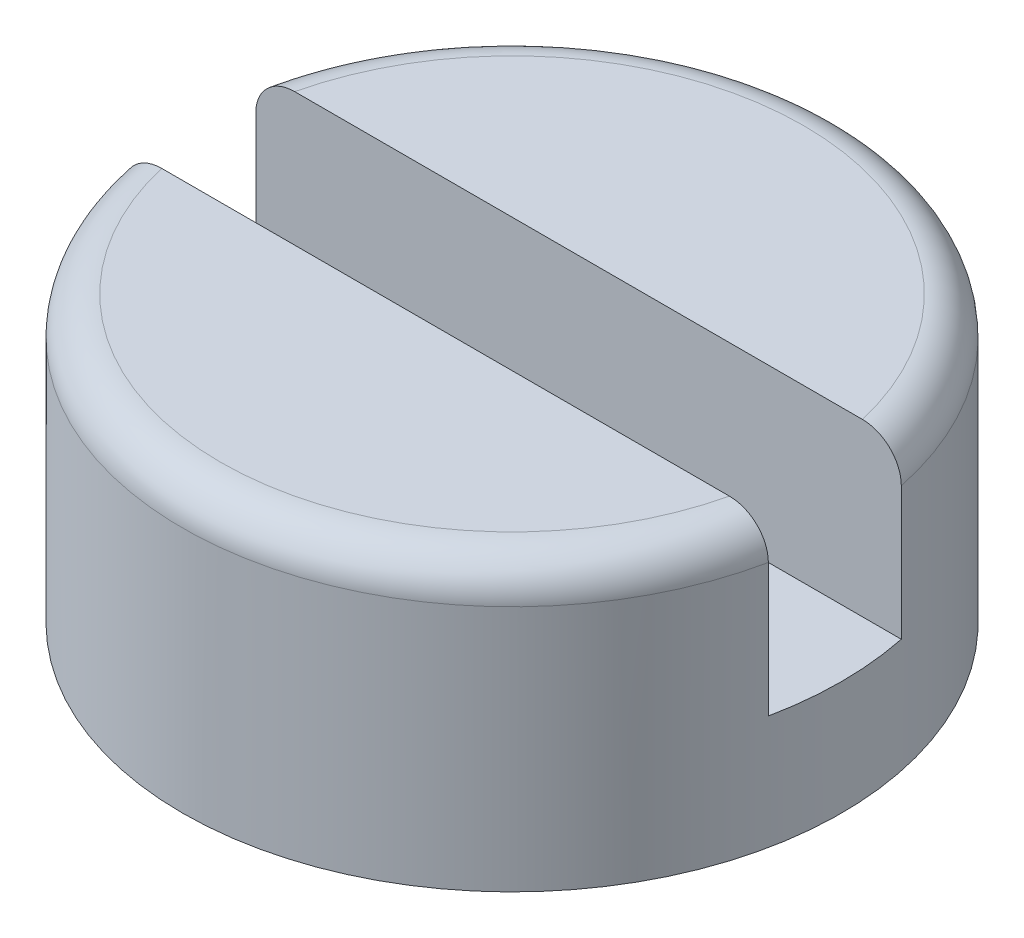
SolidWorks part; units mm, degrees
ref_plane "Спереди" through (0, 0, 0) normal (0, 0, 1) x (1, 0, 0)
ref_plane "Сверху" through (0, 0, 0) normal (0, 1, 0) x (1, 0, 0)
ref_plane "Справа" through (0, 0, 0) normal (1, 0, 0) x (0, 0, -1)
sketch "Эскиз1" plane through (0, 0, 0) normal (0, 1, 0) x (1, 0, 0)
  circle A0 centre (0, 0) radius 1.735
  dimension "D1" = 3.47
extrude "Бобышка-Вытянуть1" add sketch "Эскиз1" along normal blind 1.5
sketch "Эскиз2" plane through (0, 1.5, 0) normal (0, 1, 0) x (1, 0, 0)
  line L1 (-1.75, 0.35) -> (1.75, 0.35)
  line L2 (-1.75, 0.35) -> (-1.75, -0.35)
  line L3 (-1.75, -0.35) -> (1.75, -0.35)
  line L4 (1.75, 0.35) -> (1.75, -0.35)
  dimension "D1" = 0.7
  dimension "D2" = 3.5
  dimension "D3" = 1.75
  dimension "D4" = 0.35
extrude "Вырез-Вытянуть1" cut sketch "Эскиз2" against normal blind 0.9
fillet "Скругление2" radius 0.2 2 edges at (0, 1.5, -1.735) (0, 1.5, 1.735)
